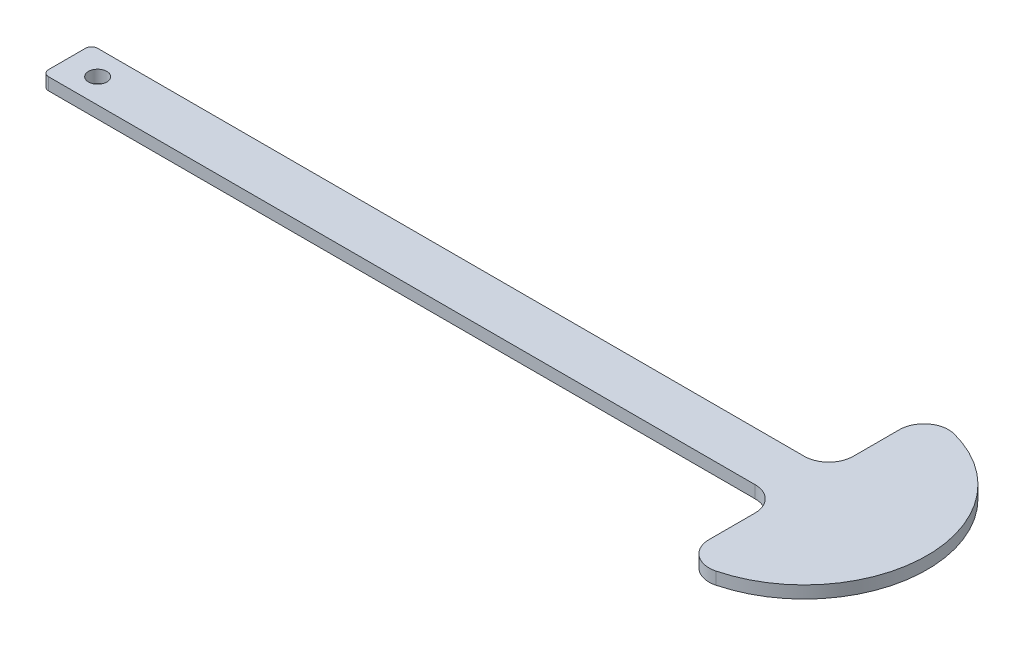
SolidWorks part; units mm, degrees
ref_plane "Front Plane" through (0, 0, 0) normal (0, 0, 1) x (1, 0, 0)
ref_plane "Top Plane" through (0, 0, 0) normal (0, 1, 0) x (1, 0, 0)
ref_plane "Right Plane" through (0, 0, 0) normal (1, 0, 0) x (0, 0, -1)
sketch "Sketch1" plane through (0, 0, 0) normal (0, 1, 0) x (1, 0, 0)
  line L0 (60, 15.4919) -> (60, 8)
  line L1 (-59, 4) -> (56, 4)
  line L2 (-60, 3) -> (-60, -3)
  line L3 (-59, -4) -> (56, -4)
  line L5 (-60, 4) -> (60, -4) construction
  line L6 (-60, -4) -> (60, 4) construction
  line L7 (60, -8) -> (60, -15.4919)
  line L8 (0, 0) -> (60, 0) construction
  line L9 (-55, 4) -> (-55, -4) construction
  arc A1 (56, -4) -> (60, -8) centre (56, -8) cw
  arc A2 (65, -19.3649) -> (65, 19.3649) centre (60, 0) ccw
  arc A3 (60, -15.4919) -> (65, -19.3649) centre (64, -15.4919) ccw
  arc A4 (60, 15.4919) -> (65, 19.3649) centre (64, 15.4919) cw
  arc A5 (56, 4) -> (60, 8) centre (56, 8) ccw
  circle A6 centre (-55, 0) radius 1.5
  arc A7 (-60, -3) -> (-59, -4) centre (-59, -3) ccw
  arc A8 (-59, 4) -> (-60, 3) centre (-59, 3) ccw
  point P0 (0, 0)
  point P7 (-55, -1.0962)
  point P11 (60, 0)
  point P17 (60, -20)
  point P23 (-53.7708, -4)
  point P28 (-55, 0)
  point P29 (-55.6118, 2.5609)
  point P30 (0, 0)
  point P31 (0, 0)
  dimension "D3" = 20
  dimension "D4" = 4
  dimension "D5" = 3
  dimension "D7" = 1
  dimension "D1" = 120
  dimension "D2" = 8
  dimension "D6" = 5
extrude "Boss-Extrude1" add sketch "Sketch1" along normal blind 2
